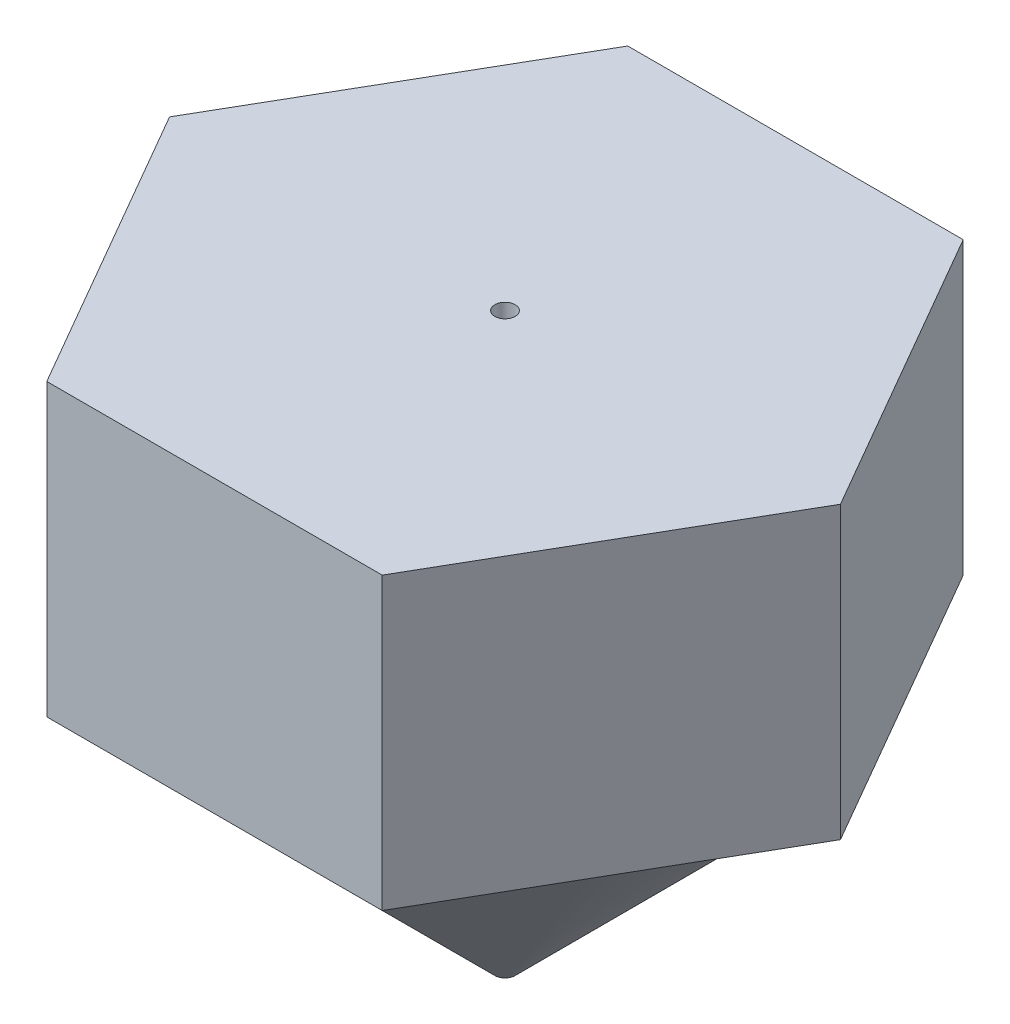
SolidWorks part; units mm, degrees
ref_plane "Front Plane" through (0, 0, 0) normal (0, 0, 1) x (1, 0, 0)
ref_plane "Top Plane" through (0, 0, 0) normal (0, 1, 0) x (1, 0, 0)
ref_plane "Right Plane" through (0, 0, 0) normal (1, 0, 0) x (0, 0, -1)
sketch "Sketch1" plane through (0, 0, 0) normal (0, 1, 0) x (1, 0, 0)
  line L1 (5.7735, 0) -> (2.8868, 5)
  line L2 (2.8868, 5) -> (-2.8868, 5)
  line L3 (-2.8868, 5) -> (-5.7735, 0)
  line L4 (-5.7735, 0) -> (-2.8868, -5)
  line L5 (-2.8868, -5) -> (2.8868, -5)
  line L6 (2.8868, -5) -> (5.7735, 0)
  circle A0 centre (0, 0) radius 5 construction
  dimension "D1" = 10
extrude "Boss-Extrude1" add sketch "Sketch1" against normal blind 5
sketch "Sketch3" plane through (0, 0, 0) normal (0, 0, 1) x (1, 0, 0)
  line L0 (0, -5) -> (0, -10)
  line L1 (-2.8868, -5) -> (2.8868, -5) construction
  line L2 (0, -10) -> (-5, -5)
  line L3 (-5.7735, -5) -> (-2.8868, -5) construction
  line L4 (-5, -5) -> (0, -5)
  dimension "D1" = 45
  dimension "D2" = 5
revolve "Revolve1" add sketch "Sketch3" angle 360 about L0
sketch "Sketch4" plane through (0, 0, 0) normal (0, 1, 0) x (1, 0, 0)
  circle A0 centre (0, 0) radius 0.175
  dimension "D1" = 0.35
extrude "Cut-Extrude1" cut sketch "Sketch4" against normal through all
